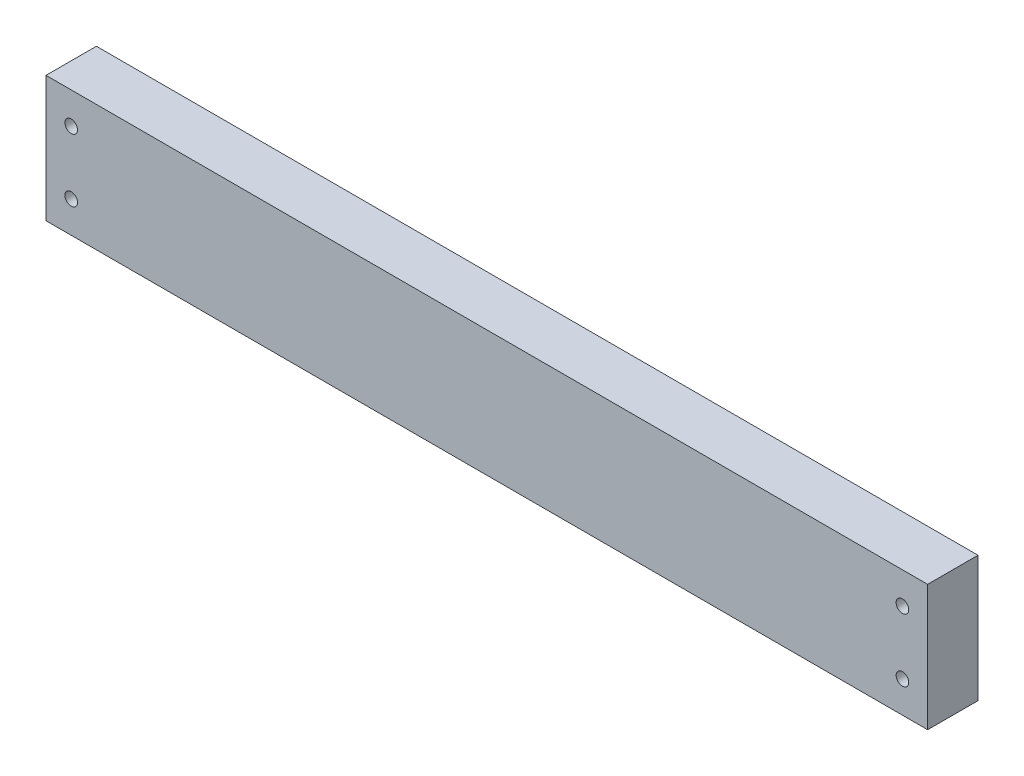
SolidWorks part; units mm, degrees
material "Kiefer"
ref_plane "Ebene vorne" through (0, 0, 0) normal (0, 0, 1) x (1, 0, 0)
ref_plane "Ebene oben" through (0, 0, 0) normal (0, 1, 0) x (1, 0, 0)
ref_plane "Ebene rechts" through (0, 0, 0) normal (1, 0, 0) x (0, 0, -1)
sketch "Skizze1" plane through (0, 0, 0) normal (1, 0, 0) x (0, 0, -1)
  line L1 (-10, 25) -> (10, 25)
  line L2 (-10, 25) -> (-10, -25)
  line L3 (-10, -25) -> (10, -25)
  line L4 (10, 25) -> (10, -25)
  line L5 (-10, 25) -> (10, -25) construction
  line L6 (-10, -25) -> (10, 25) construction
  point P0 (0, 0)
  dimension "D1" = 50
  dimension "D2" = 20
extrude "Aufsatz-Linear austragen1" add sketch "Skizze1" along normal blind 350
sketch "Skizze2" plane through (0, 0, 10) normal (0, 0, 1) x (1, 0, 0)
  line L1 (350, -25) -> (0, -25) construction
  line L2 (350, 25) -> (350, -25) construction
  line L3 (0, 0) -> (20, 0) construction
  line L4 (0, 0) -> (0, -25) construction
  line L5 (0, -25) -> (20, -25) construction
  line L6 (20, 0) -> (20, -25) construction
  line L7 (0, 0) -> (20, -25) construction
  line L8 (350, 0) -> (330, 0) construction
  line L9 (0, -25) -> (20, 0) construction
  line L10 (350, 0) -> (350, -25) construction
  line L11 (350, -25) -> (330, -25) construction
  line L12 (330, 0) -> (330, -25) construction
  line L13 (350, 0) -> (330, -25) construction
  line L14 (350, -25) -> (330, 0) construction
  line L15 (0, 25) -> (20, 25) construction
  line L16 (0, 25) -> (0, 0) construction
  line L17 (0, 0) -> (20, 0) construction
  line L18 (20, 25) -> (20, 0) construction
  line L19 (0, 25) -> (20, 0) construction
  line L20 (0, 0) -> (20, 25) construction
  line L21 (350, 25) -> (330, 25) construction
  line L22 (350, 25) -> (350, 0) construction
  line L23 (350, 0) -> (330, 0) construction
  line L24 (330, 25) -> (330, 0) construction
  line L25 (350, 25) -> (330, 0) construction
  line L26 (350, 0) -> (330, 25) construction
  circle A0 centre (10, -12.5) radius 2.5
  circle A1 centre (10, 12.5) radius 2.5
  circle A2 centre (340, -12.5) radius 2.5
  circle A3 centre (340, 12.5) radius 2.5
  point P4 (10, -12.5)
  point P12 (10, 12.5)
  point P19 (340, -12.5)
  point P26 (340, 12.5)
  dimension "D2" = 5
  dimension "D1" = 20
extrude "Schnitt-Linear austragen1" cut sketch "Skizze2" against normal through all
